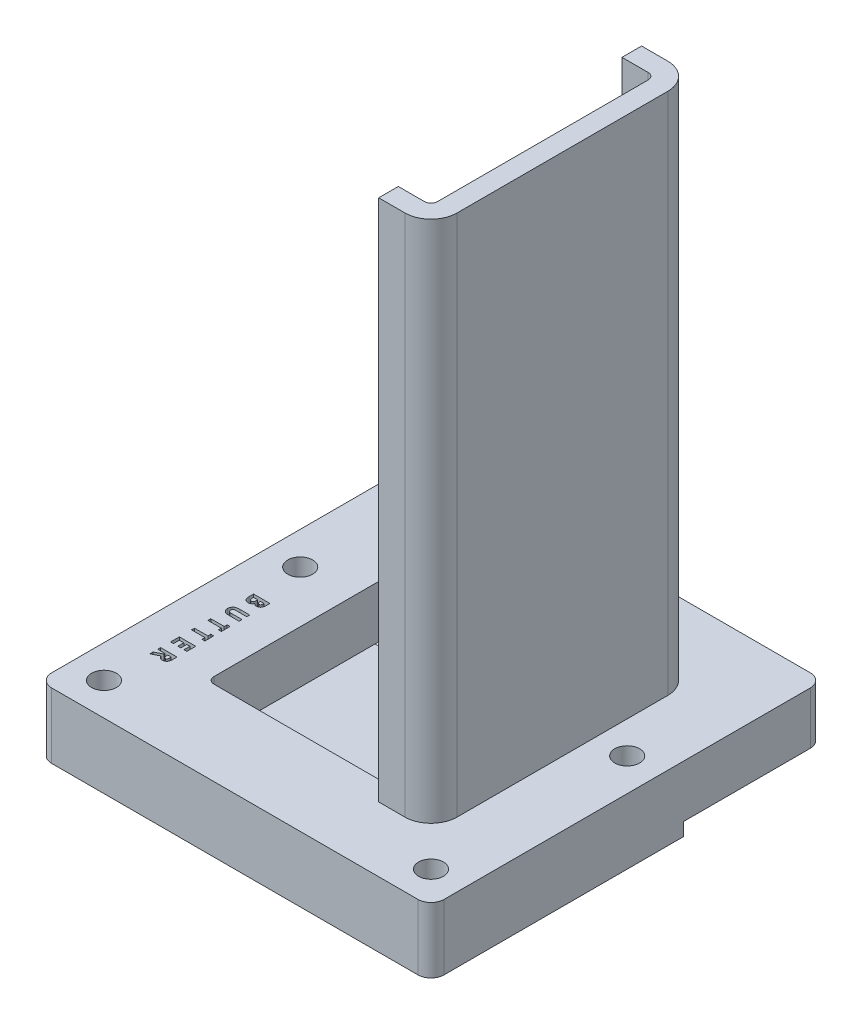
SolidWorks part; units mm, degrees
ref_plane "Front Plane" through (0, 0, 0) normal (0, 0, 1) x (1, 0, 0)
ref_plane "Top Plane" through (0, 0, 0) normal (0, 1, 0) x (1, 0, 0)
ref_plane "Right Plane" through (0, 0, 0) normal (1, 0, 0) x (0, 0, -1)
sketch "Sketch1" plane through (0, 0, 0) normal (0, 1, 0) x (1, 0, 0)
  line L1 (-38.1, -38.1) -> (38.1, -38.1)
  line L2 (-38.1, -38.1) -> (-38.1, 38.1)
  line L3 (-38.1, 38.1) -> (38.1, 38.1)
  line L4 (38.1, -38.1) -> (38.1, 38.1)
  line L5 (-38.1, -38.1) -> (38.1, 38.1) construction
  line L6 (-38.1, 38.1) -> (38.1, -38.1) construction
  point P0 (0, 0)
  dimension "D1" = 76.2
  dimension "D2" = 76.2
extrude "Boss-Extrude1" add sketch "Sketch1" along normal blind 12.7
sketch "Sketch2" plane through (0, 12.7, 0) normal (0, 1, 0) x (1, 0, 0)
  line L1 (-21.717, -21.717) -> (21.717, -21.717)
  line L2 (-21.717, -21.717) -> (-21.717, 21.717)
  line L3 (-21.717, 21.717) -> (21.717, 21.717)
  line L4 (21.717, -21.717) -> (21.717, 21.717)
  line L5 (-21.717, -21.717) -> (21.717, 21.717) construction
  line L6 (-21.717, 21.717) -> (21.717, -21.717) construction
  point P0 (0, 0)
  dimension "D1" = 43.434
  dimension "D2" = 43.434
extrude "Cut-Extrude1" cut sketch "Sketch2" against normal blind 10.16
fillet "Fillet1" radius 1.27 4 edges at (-21.717, 7.62, 21.717) (21.717, 7.62, 21.717) (21.717, 7.62, -21.717) (-21.717, 7.62, -21.717)
sketch "Sketch3" plane through (0, 2.54, 0) normal (0, 1, 0) x (1, 0, 0)
  line L0 (-21.717, 10.8585) -> (21.717, 10.8585)
  line L2 (-21.717, 10.8585) -> (-21.717, 20.447)
  line L3 (-20.447, 21.717) -> (20.447, 21.717)
  line L4 (21.717, 10.8585) -> (21.717, 20.447)
  line L5 (0, 0) -> (21.717, 21.717) construction
  line L6 (-21.717, 21.717) -> (0, 0) construction
  arc A0 (20.447, 21.717) -> (21.717, 20.447) centre (20.447, 20.447) cw
  arc A1 (-20.447, 21.717) -> (-21.717, 20.447) centre (-20.447, 20.447) ccw
  point P0 (0, 0)
  dimension "D2" = 1.27
  dimension "D1" = 10.8585
extrude "Cut-Extrude2" cut sketch "Sketch3" against normal through all
sketch "Sketch4" plane through (0, 12.7, 0) normal (0, 1, 0) x (1, 0, 0)
  line L1 (-31.75, -31.75) -> (31.75, -31.75) construction
  line L2 (-31.75, -31.75) -> (-31.75, 31.75) construction
  line L3 (-31.75, 31.75) -> (31.75, 31.75) construction
  line L4 (31.75, -31.75) -> (31.75, 31.75) construction
  line L5 (-31.75, -31.75) -> (31.75, 31.75) construction
  line L6 (-31.75, 31.75) -> (31.75, -31.75) construction
  circle A2 centre (31.75, -31.75) radius 2.413
  circle A3 centre (-31.75, -31.75) radius 2.413
  circle A4 centre (-31.75, 6.35) radius 2.413
  circle A5 centre (31.75, 6.35) radius 2.413
  point P0 (0, 0)
  dimension "D3" = 4.826
  dimension "D4" = 4.826
  dimension "D5" = 4.826
  dimension "D6" = 4.826
  dimension "D1" = 63.5
  dimension "D2" = 63.5
  dimension "D7" = 38.1
  dimension "D8" = 38.1
extrude "Cut-Extrude3" cut sketch "Sketch4" against normal through all
fillet "Fillet2" radius 2.54 4 edges at (-38.1, 6.35, 38.1) (38.1, 6.35, 38.1) (38.1, 6.35, -38.1) (-38.1, 6.35, -38.1)
sketch "Sketch5" plane through (0, 0, 0) normal (0, -1, 0) x (1, 0, 0)
  line L0 (38.1, 35.56) -> (38.1, -35.56) construction
  line L1 (38.1, -10.922) -> (-38.1, -10.922)
  line L2 (38.1, -10.922) -> (38.1, -38.1)
  line L3 (38.1, -38.1) -> (-38.1, -38.1)
  line L4 (-38.1, -10.922) -> (-38.1, -38.1)
  line L5 (35.56, -38.1) -> (-35.56, -38.1) construction
  dimension "D1" = 27.178
  dimension "D2" = 0
extrude "Cut-Extrude4" cut sketch "Sketch5" against normal blind 2.54
sketch "Sketch6" plane through (0, 12.7, 0) normal (0, 1, 0) x (1, 0, 0)
  line L0 (21.717, 20.447) -> (21.717, -20.447)
  line L1 (20.447, 21.717) -> (15.367, 21.717)
  line L2 (20.447, 21.717) -> (-20.447, 21.717) construction
  line L3 (15.367, 21.717) -> (15.367, 25.527)
  line L4 (15.367, 25.527) -> (20.447, 25.527)
  line L5 (25.527, 20.447) -> (25.527, -20.447)
  line L6 (0, 0) -> (11.484, 0) construction
  line L8 (15.367, -21.717) -> (15.367, -25.527)
  line L9 (20.447, -21.717) -> (15.367, -21.717)
  line L10 (15.367, -25.527) -> (20.447, -25.527)
  arc A0 (21.717, 20.447) -> (20.447, 21.717) centre (20.447, 20.447) ccw
  arc A1 (21.717, 20.447) -> (20.447, 21.717) centre (20.447, 20.447) ccw construction
  arc A2 (20.447, 25.527) -> (25.527, 20.447) centre (20.447, 20.447) cw
  arc A3 (20.447, -25.527) -> (25.527, -20.447) centre (20.447, -20.447) ccw
  arc A4 (21.717, -20.447) -> (20.447, -21.717) centre (20.447, -20.447) cw
  dimension "D1" = 3.81
  dimension "D2" = 3.81
  dimension "D3" = 6.35
extrude "Boss-Extrude2" add sketch "Sketch6" along normal blind 101.6
sketch "Sketch7" plane through (0, 12.7, 0) normal (0, 1, 0) x (1, 0, 0)
  line L0 (-31.75, 0) -> (-31.75, -25.4) construction
  line L2 (-38.1, 35.56) -> (-38.1, -35.56) construction
  circle A0 centre (-31.75, 6.35) radius 2.413 construction
  circle A1 centre (-31.75, -31.75) radius 2.413 construction
  text T0 "<b>BUTTER</b>" font "Century Gothic" height 3.175
  dimension "D1" = 6.35
  dimension "D2" = 6.35
  dimension "D3" = 6.35
extrude "Cut-Extrude5" cut sketch "Sketch7" against normal blind 1.27
